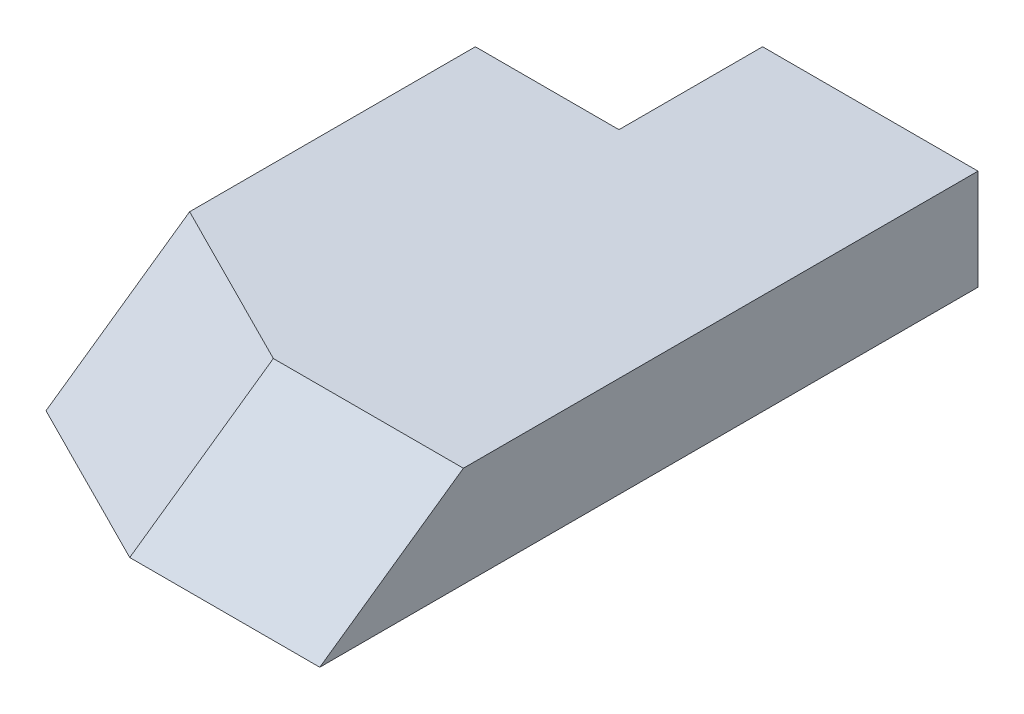
SolidWorks part; units mm, degrees
material "Plástico personalizado"
ref_plane "Front Plane" through (0, 0, 0) normal (0, 0, 1) x (1, 0, 0)
ref_plane "Top Plane" through (0, 0, 0) normal (0, 1, 0) x (1, 0, 0)
ref_plane "Right Plane" through (0, 0, 0) normal (1, 0, 0) x (0, 0, -1)
sketch "Sketch1" plane through (0, 0, 0) normal (1, 0, 0) x (0, 0, -1)
  line L0 (-28, -7) -> (15, -7)
  line L1 (15, -7) -> (15, -15.4025)
  line L5 (-28, -7) -> (-40, -15.4025)
  line L6 (-40, -15.4025) -> (15, -15.4025)
  dimension "D1" = 35
  dimension "D2" = 55
extrude "Boss-Extrude1" add sketch "Sketch1" along normal mid plane 30
ref_plane "Plane1" through (-15, -7, 28) normal (-1, 0, 0) x (0, 0, 1)
sketch "Sketch3" plane through (0, -7, 0) normal (0, 1, 0) x (1, 0, 0)
  line L0 (15, -28) -> (-15, -28) construction
  line L1 (-0.88, -28) -> (-15, -20.8768)
  line L2 (-15, 15) -> (-15, -28) construction
  point P0 (-0.88, -28)
  point P1 (0, -28)
  dimension "D1" = 0.88
  dimension "D2" = 26.77
sketch "Sketch4" plane through (0, 8.4586, 5.9228) normal (0, 0.8192, 0.5736) x (1, 0, 0)
  line L0 (-0.88, -26.9513) -> (-0.88, -41.6006) construction
  line L1 (15, -41.6006) -> (-15, -41.6006) construction
  point P6 (-0.88, -41.6006)
ref_plane "Plane2" through (-2.8251, 7.9976, 5.6) normal (-0.278, 0.7869, 0.551) x (0.9606, 0.2277, 0.1594)
sketch "Sketch5" plane through (-2.8251, 7.9976, 5.6) normal (-0.278, 0.7869, 0.551) x (0.9606, 0.2277, 0.1594)
  line L1 (-26.9188, -7.6222) -> (-29.1864, -42.3527)
  line L2 (-29.1864, -42.3527) -> (-0.2428, -61.6818)
  line L3 (-0.2428, -61.6818) -> (30.9685, -46.2804)
  line L4 (30.9685, -46.2804) -> (33.2362, -11.5499)
  line L5 (33.2362, -11.5499) -> (4.2925, 7.7792)
  line L6 (4.2925, 7.7792) -> (-26.9188, -7.6222)
  circle A0 centre (2.0249, -26.9513) radius 30.1415 construction
extrude "Cut-Extrude1" cut sketch "Sketch5" along normal blind 9
sketch "Sketch6" plane through (0, -15.4025, 0) normal (0, -1, 0) x (1, 0, 0)
  line L0 (-15, 32.8768) -> (-15, -15) construction
  line L1 (-15, -3) -> (-3, -3)
  line L2 (-15, -3) -> (-15, -15)
  line L3 (-15, -15) -> (-3, -15)
  line L4 (-3, -3) -> (-3, -15)
  line L5 (15, -15) -> (-15, -15) construction
  dimension "D1" = 12
  dimension "D2" = 12
extrude "Cut-Extrude2" cut sketch "Sketch6" against normal blind 10
hole_wizard "Escareado para parafuso de máquina com cabeça chata de M51" positions "Esboço1" profile "Esboço2" countersink size "M5" standard "Ansi Metric"
sketch "Esboço1" plane through (40.125, -15.4025, -23.4602) normal (0, -1, 0) x (-1, 0, 0)
  line L4 (0, 0) -> (0, -35.8382) construction
  point P0 (33.065, -33.4602)
  point P2 (33.065, -18.4602)
  point P28 (-33.065, -18.4602)
  point P29 (-33.065, -33.4602)
  point P30 (-33.065, -33.4602)
  point P32 (-33.065, -18.4602)
sketch "Esboço2" plane through (7.06, -15.4025, 10) normal (1, 0, 0) x (0, 0, -1)
  line L0 (0, 0) -> (0, 21.6524)
  line L1 (0, 21.6524) -> (2.75, 20)
  line L2 (2.75, 20) -> (2.75, 2.45)
  line L3 (2.75, 2.45) -> (5.2, 0)
  line L4 (5.2, 0) -> (0, 0)
  line L5 (-2.75, 2.45) -> (-5.2, 0) construction
  line L6 (0, 21.6524) -> (-2.75, 20) construction
  line L7 (0, -6.35) -> (0, 107.95) construction
  dimension "Hole Dia." = 5.5
  dimension "Hole Depth" = 20
  dimension "Near C'Sink Dia." = 10.4
  dimension "Near C'Sink Angle" = 90
  dimension "Drill Angle" = 118
